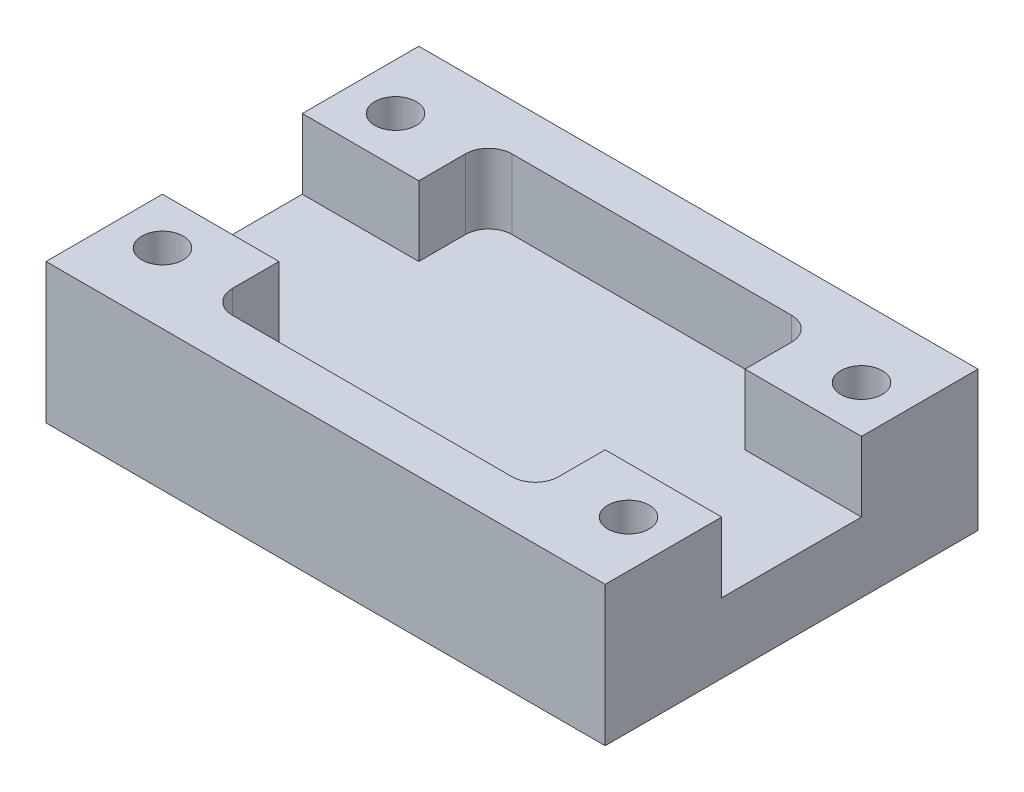
SolidWorks part; units mm, degrees
ref_plane "Front Plane" through (0, 0, 0) normal (0, 0, 1) x (1, 0, 0)
ref_plane "Top Plane" through (0, 0, 0) normal (0, 1, 0) x (1, 0, 0)
ref_plane "Right Plane" through (0, 0, 0) normal (1, 0, 0) x (0, 0, -1)
sketch "Sketch1" plane through (0, 0, 0) normal (0, 1, 0) x (1, 0, 0)
  line L1 (-12, -8) -> (12, -8)
  line L2 (-12, -8) -> (-12, 8)
  line L3 (-12, 8) -> (12, 8)
  line L4 (12, -8) -> (12, 8)
  line L5 (-12, -8) -> (12, 8) construction
  line L6 (-12, 8) -> (12, -8) construction
  point P0 (0, 0)
  dimension "D1" = 16
  dimension "D2" = 24
extrude "Boss-Extrude1" add sketch "Sketch1" along normal blind 6
sketch "Sketch2" plane through (0, 6, 0) normal (0, 1, 0) x (1, 0, 0)
  line L0 (12, 0) -> (-12, 0) construction
  line L1 (-7, -6) -> (7, -6)
  line L2 (-7, -6) -> (-7, 6)
  line L3 (-7, 6) -> (7, 6)
  line L4 (7, -6) -> (7, 6)
  line L5 (-7, -6) -> (7, 6) construction
  line L6 (-7, 6) -> (7, -6) construction
  line L7 (12, -8) -> (12, 8) construction
  line L8 (-12, 8) -> (-12, -8) construction
  line L10 (12, -3) -> (7, -3)
  line L11 (12, -3) -> (12, 3)
  line L12 (12, 3) -> (7, 3)
  line L13 (7, -3) -> (7, 3)
  line L14 (12, -3) -> (7, 3) construction
  line L15 (12, 3) -> (7, -3) construction
  line L16 (-12, -3) -> (-7, -3)
  line L17 (-12, -3) -> (-12, 3)
  line L18 (-12, 3) -> (-7, 3)
  line L19 (-7, -3) -> (-7, 3)
  line L20 (-12, -3) -> (-7, 3) construction
  line L21 (-12, 3) -> (-7, -3) construction
  point P0 (0, 0)
  point P12 (9.5, 0)
  point P18 (-9.5, 0)
  line M10 (12, -8) -> (12, 8)
  line M12 (-12, 8) -> (-12, -8)
  dimension "D1" = 12
  dimension "D2" = 14
  dimension "D3" = 6
  dimension "D4" = 6
extrude "Cut-Extrude1" cut sketch "Sketch2" against normal blind 3 contours L18 L16 L2 M12 | L1 L4 L3 L2 | L12 L4 L10 M10
fillet "Fillet1" radius 1 4 edges at (7, 4.5, -6) (7, 4.5, 6) (-7, 4.5, 6) (-7, 4.5, -6)
sketch "Sketch3" plane through (0, 6, 0) normal (0, 1, 0) x (1, 0, 0)
  line L1 (-10, -5) -> (10, -5) construction
  line L2 (-10, -5) -> (-10, 5) construction
  line L3 (-10, 5) -> (10, 5) construction
  line L4 (10, -5) -> (10, 5) construction
  line L5 (-10, -5) -> (10, 5) construction
  line L6 (-10, 5) -> (10, -5) construction
  circle A0 centre (-10, 5) radius 0.889
  circle A1 centre (-10, -5) radius 0.889
  circle A2 centre (10, -5) radius 0.889
  circle A3 centre (10, 5) radius 0.889
  point P0 (0, 0)
  dimension "D3" = 1.778
  dimension "D4" = 1.778
  dimension "D5" = 1.778
  dimension "D6" = 1.778
  dimension "D1" = 10
  dimension "D2" = 20
extrude "Cut-Extrude2" cut sketch "Sketch3" against normal through all
